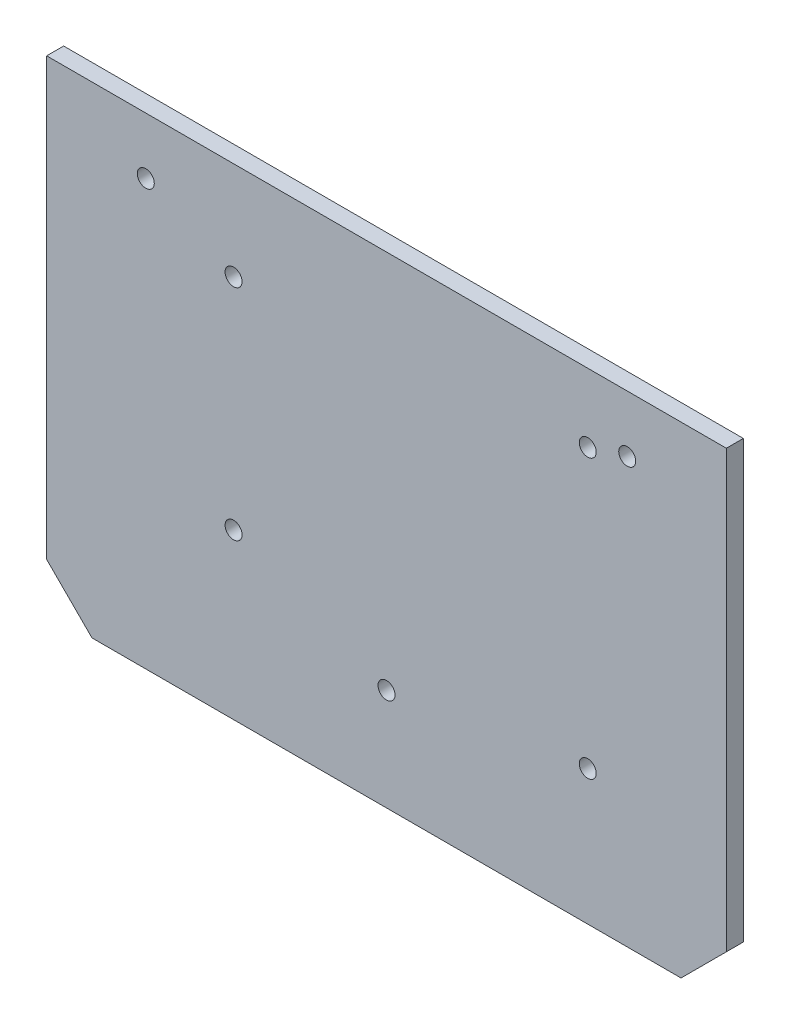
SolidWorks part; units mm, degrees
ref_plane "前视基准面" through (0, 0, 0) normal (0, 0, 1) x (1, 0, 0)
ref_plane "上视基准面" through (0, 0, 0) normal (0, 1, 0) x (1, 0, 0)
ref_plane "右视基准面" through (0, 0, 0) normal (1, 0, 0) x (0, 0, -1)
sketch "草图1" plane through (0, 0, 0) normal (0, 0, 1) x (1, 0, 0)
  line L1 (-60, 42.5) -> (60, 42.5)
  line L2 (-60, 42.5) -> (-60, -42.5)
  line L3 (-60, -42.5) -> (60, -42.5)
  line L4 (60, 42.5) -> (60, -42.5)
  line L5 (-60, 42.5) -> (60, -42.5) construction
  line L6 (-60, -42.5) -> (60, 42.5) construction
  point P0 (0, 0)
  dimension "D1" = 120
  dimension "D2" = 85
extrude "凸台-拉伸1" add sketch "草图1" along normal blind 3
sketch "草图2" plane through (0, 0, 3) normal (0, 0, 1) x (1, 0, 0)
  line L0 (0, 42.5) -> (0, -42.5) construction
  line L1 (60, 42.5) -> (-60, 42.5) construction
  line L2 (-60, -42.5) -> (60, -42.5) construction
  circle A0 centre (0, -24.5) radius 1.5
  circle A1 centre (-42.5, 32.5) radius 1.5
  circle A3 centre (42.5, 32.5) radius 1.5
  dimension "D1" = 18
  dimension "D2" = 85
  dimension "D3" = 75
  dimension "D4" = 3
  dimension "D5" = 3
extrude "切除-拉伸1" cut sketch "草图2" against normal through all
sketch "草图3" plane through (0, 0, 3) normal (0, 0, 1) x (1, 0, 0)
  line L0 (-78.7536, 5.85) -> (99.3327, 5.85) construction
  line L1 (-60, -42.5) -> (60, -42.5) construction
  line L2 (-60, 42.5) -> (-60, -42.5) construction
  circle A0 centre (35.528, 30.4) radius 1.5
  circle A1 centre (-27, 25.2) radius 1.5
  circle A2 centre (35.528, -18.7) radius 1.5
  circle A3 centre (-27, -13.5) radius 1.5
  point P10 (18.1181, -13.8711)
  point P11 (31.4593, -16.009)
  point P12 (26.902, -15.5532)
  point P13 (31.2314, -15.5532)
  point P14 (31.6872, -13.9582)
  point P15 (29.4085, -14.4139)
  point P16 (26.902, -14.1861)
  point P17 (-31.2192, -19.1839)
  point P18 (-27.5313, -17.3311)
  dimension "D1" = 38.7
  dimension "D2" = 49.1
  dimension "D3" = 76.4
  dimension "D4" = 3
  dimension "D5" = 29
  dimension "D6" = 33
extrude "切除-拉伸2" cut sketch "草图3" against normal through all
chamfer "倒角1" distance 8 angle 45 2 edges at (60, -42.5, 1.5) (-60, -42.5, 1.5)
